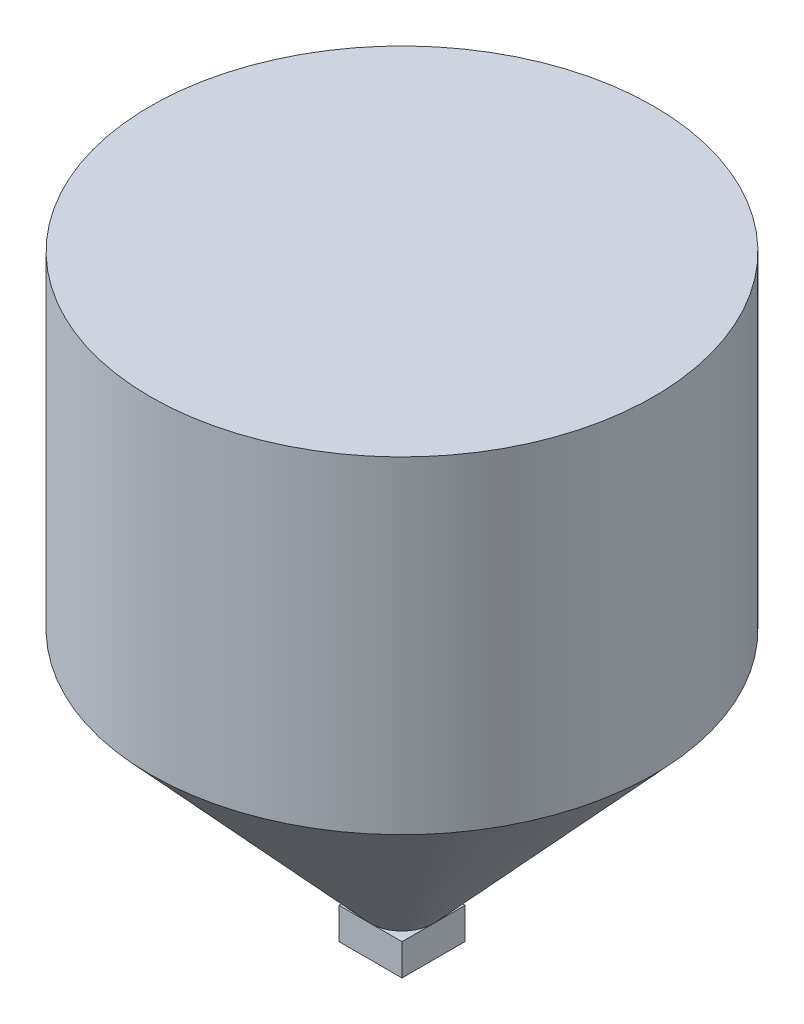
SolidWorks part; units mm, degrees
ref_plane "Alzado" through (0, 0, 0) normal (0, 0, 1) x (1, 0, 0)
ref_plane "Planta" through (0, 0, 0) normal (0, 1, 0) x (1, 0, 0)
ref_plane "Vista lateral" through (0, 0, 0) normal (1, 0, 0) x (0, 0, -1)
sketch "Croquis1" plane through (0, 0, 0) normal (0, 1, 0) x (1, 0, 0)
  circle A0 centre (0, 0) radius 400
  dimension "D1" = 800
ref_plane "Plano1" through (0, -900, 0) normal (0, 1, 0) x (1, 0, 0)
extrude "Saliente-Extruir1" add sketch "Croquis1" against normal blind 520 contours A0
sketch "Croquis2" plane through (0, -520, 0) normal (0, -1, 0) x (1, 0, 0)
  circle A0 centre (0, 0) radius 400
  dimension "D1" = 800
sketch "Croquis3" plane through (0, -900, 0) normal (0, 1, 0) x (1, 0, 0)
  circle A0 centre (0, 0) radius 50
  dimension "D1" = 100
loft "Recubrir1" add profiles "Croquis3", "Croquis2"
sketch "Croquis4" plane through (0, -900, 0) normal (0, -1, 0) x (1, 0, 0)
  line L1 (-50, -50) -> (50, -50)
  line L2 (-50, -50) -> (-50, 50)
  line L3 (-50, 50) -> (50, 50)
  line L4 (50, -50) -> (50, 50)
extrude "Saliente-Extruir2" add sketch "Croquis4" along normal blind 50
